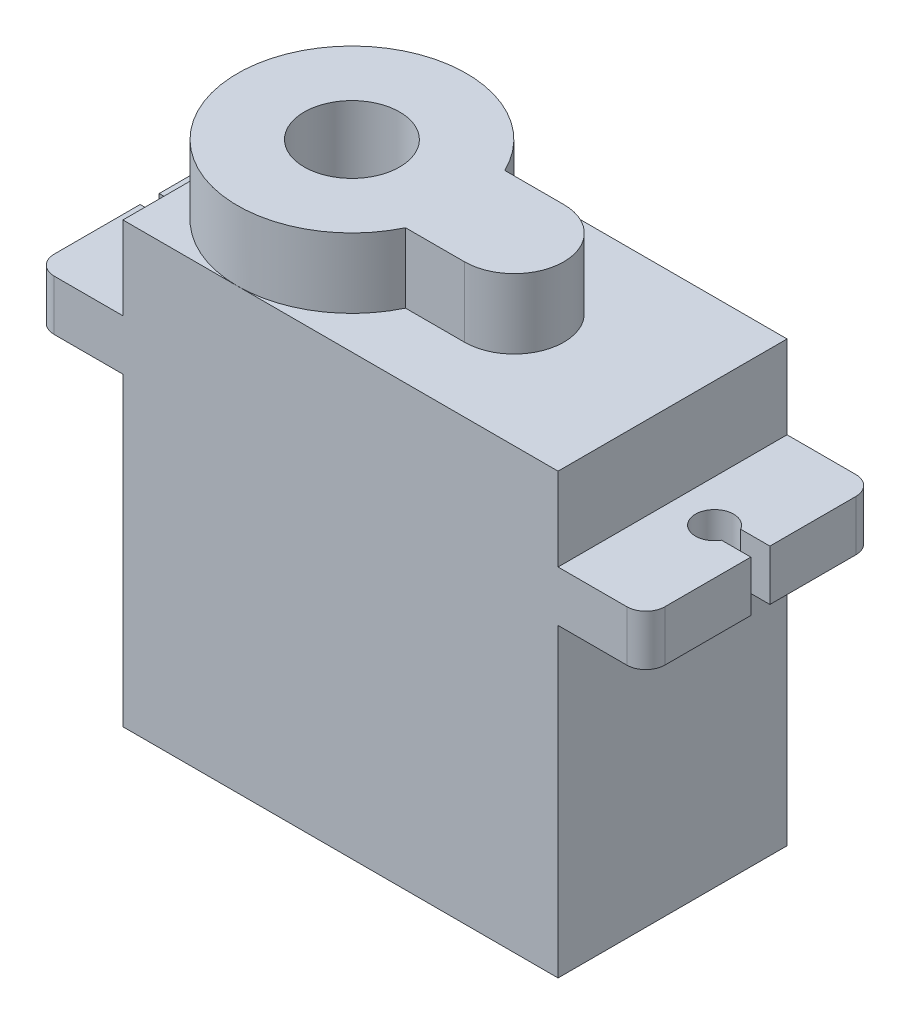
SolidWorks part; units mm, degrees
material "Acrylic (Medium-high impact)"
ref_plane "Plano frontal" through (0, 0, 0) normal (0, 0, 1) x (1, 0, 0)
ref_plane "Plano superior" through (0, 0, 0) normal (0, 1, 0) x (1, 0, 0)
ref_plane "Plano direito" through (0, 0, 0) normal (1, 0, 0) x (0, 0, -1)
sketch "Sketch1" plane through (0, 0, 0) normal (0, 1, 0) x (1, 0, 0)
  line L1 (-11.4, -6) -> (11.4, -6)
  line L2 (-11.4, -6) -> (-11.4, 6)
  line L3 (-11.4, 6) -> (11.4, 6)
  line L4 (11.4, -6) -> (11.4, 6)
  line L5 (-11.4, -6) -> (11.4, 6) construction
  line L6 (-11.4, 6) -> (11.4, -6) construction
  point P0 (0, 0)
  dimension "D1" = 12
  dimension "D2" = 22.8
extrude "Boss-Extrude1" add sketch "Sketch1" against normal blind 16
sketch "Sketch2" plane through (0, 0, 0) normal (0, 1, 0) x (1, 0, 0)
  line L0 (11.4, 6) -> (-11.4, 6) construction
  line L1 (-16, -6) -> (16, -6)
  line L2 (-16, -6) -> (-16, 6)
  line L3 (-16, 6) -> (16, 6)
  line L4 (16, -6) -> (16, 6)
  line L5 (-16, -6) -> (16, 6) construction
  line L6 (-16, 6) -> (16, -6) construction
  point P0 (0, 0)
  dimension "D1" = 32
extrude "Boss-Extrude2" add sketch "Sketch2" along normal blind 2.65
sketch "Sketch3" plane through (0, 0, 0) normal (0, 0, 1) x (1, 0, 0)
  line L0 (11.4, -16) -> (11.4, 0) construction
  line L1 (-11.4, -16) -> (11.4, -16)
  line L2 (-11.4, -16) -> (-11.4, 7)
  line L3 (-11.4, 7) -> (11.4, 7)
  line L4 (11.4, -16) -> (11.4, 7)
  dimension "D1" = 23
extrude "Boss-Extrude3" add sketch "Sketch3" along normal up to surface and the other way up to surface up to face at (0, -3.3375, 6) other way up to face at (0, -3.3375, -6)
sketch "Sketch4" plane through (0, 2.65, 0) normal (0, 1, 0) x (1, 0, 0)
  line L0 (-11.4, 6) -> (-11.4, -6) construction
  line L1 (11.4, -6) -> (11.4, 6) construction
  line L2 (-16, 6) -> (-16, -6) construction
  line L3 (-16, 0.5) -> (-13.6, 0.5)
  line L4 (-16, 0.5) -> (-16, -0.5)
  line L5 (-16, -0.5) -> (-13.6, -0.5)
  line L6 (-13.6, 0.5) -> (-13.6, -0.5)
  line L7 (16, -6) -> (16, 6) construction
  line L8 (16, 0.5) -> (13.6, 0.5)
  line L9 (16, 0.5) -> (16, -0.5)
  line L10 (16, -0.5) -> (13.6, -0.5)
  line L11 (13.6, 0.5) -> (13.6, -0.5)
  circle A0 centre (13.6, 0) radius 1
  circle A1 centre (-13.6, 0) radius 1
  line M5 (-16, 6) -> (-16, -6)
  dimension "D3" = 2
  dimension "D4" = 2
  dimension "D1" = 25
  dimension "D2" = 25
  dimension "D5" = 1
  dimension "D6" = 1
extrude "Cut-Extrude1" cut sketch "Sketch4" against normal up to next contours L8 A0 L10 L11 | L10 A0 L8 L11 | A0 L10 L9 L8 | A1 L3 L5 M5 | L3 A1 L5 L6 | L5 A1 L3 L6
fillet "Fillet1" radius 1 4 edges at (16, 1.325, -6) (16, 1.325, 6) (-16, 1.325, -6) (-16, 1.325, 6)
sketch "Sketch5" plane through (0, 7, 0) normal (0, 1, 0) x (1, 0, 0)
  line L0 (11.4, 6) -> (-11.4, 6) construction
  line L1 (-11.4, 6) -> (-11.4, -6) construction
  circle A0 centre (-5.4, 0) radius 6
extrude "Boss-Extrude4" add sketch "Sketch5" along normal blind 3.65
sketch "Sketch6" plane through (0, 7, 0) normal (0, 1, 0) x (1, 0, 0)
  line L0 (-11.4, -6) -> (-11.4, 0) construction
  line L1 (3.1, 2.6) -> (0.0074, 2.6)
  line L2 (3.1, -2.6) -> (0.0074, -2.6)
  circle A0 centre (3.1, 0) radius 2.6
  circle A1 centre (-5.4, 0) radius 6 construction
  circle A2 centre (-5.4, 0) radius 6
  arc M2 (-5.4, 6) -> (-5.4, -6) centre (-5.4, 0) cw
  dimension "D2" = 5.2
  dimension "D1" = 14.5
extrude "Boss-Extrude5" add sketch "Sketch6" along normal blind 3.65 contours A0 L2 M2 | A0 L1 M2 | A0 M2
sketch "Sketch7" plane through (0, 10.65, 0) normal (0, 1, 0) x (1, 0, 0)
  circle A0 centre (-5.4, 0) radius 2.5
  dimension "D1" = 5
extrude "Cut-Extrude2" cut sketch "Sketch7" against normal up to surface (3.65 mm away) up to face at (2.7244, 7, 0)
sketch "Sketch8" plane through (-11.4, 0, 0) normal (-1, 0, 0) x (0, 0, 1)
  line L0 (-6, -16) -> (6, -16) construction
  line L1 (-1.5, -10.6) -> (1.5, -10.6)
  line L2 (-1.5, -10.6) -> (-1.5, -9.6)
  line L3 (-1.5, -9.6) -> (1.5, -9.6)
  line L4 (1.5, -10.6) -> (1.5, -9.6)
  line L5 (-1.5, -10.6) -> (1.5, -9.6) construction
  line L6 (-1.5, -9.6) -> (1.5, -10.6) construction
  point P0 (0, -10.1)
  dimension "D1" = 6.4
  dimension "D2" = 1
  dimension "D3" = 3
extrude "Boss-Extrude6" add sketch "Sketch8" along normal blind 3
equation "\"D2@Sketch4\"=\"D1@Sketch4\""
equation "\"D4@Sketch4\"=\"D3@Sketch4\""
